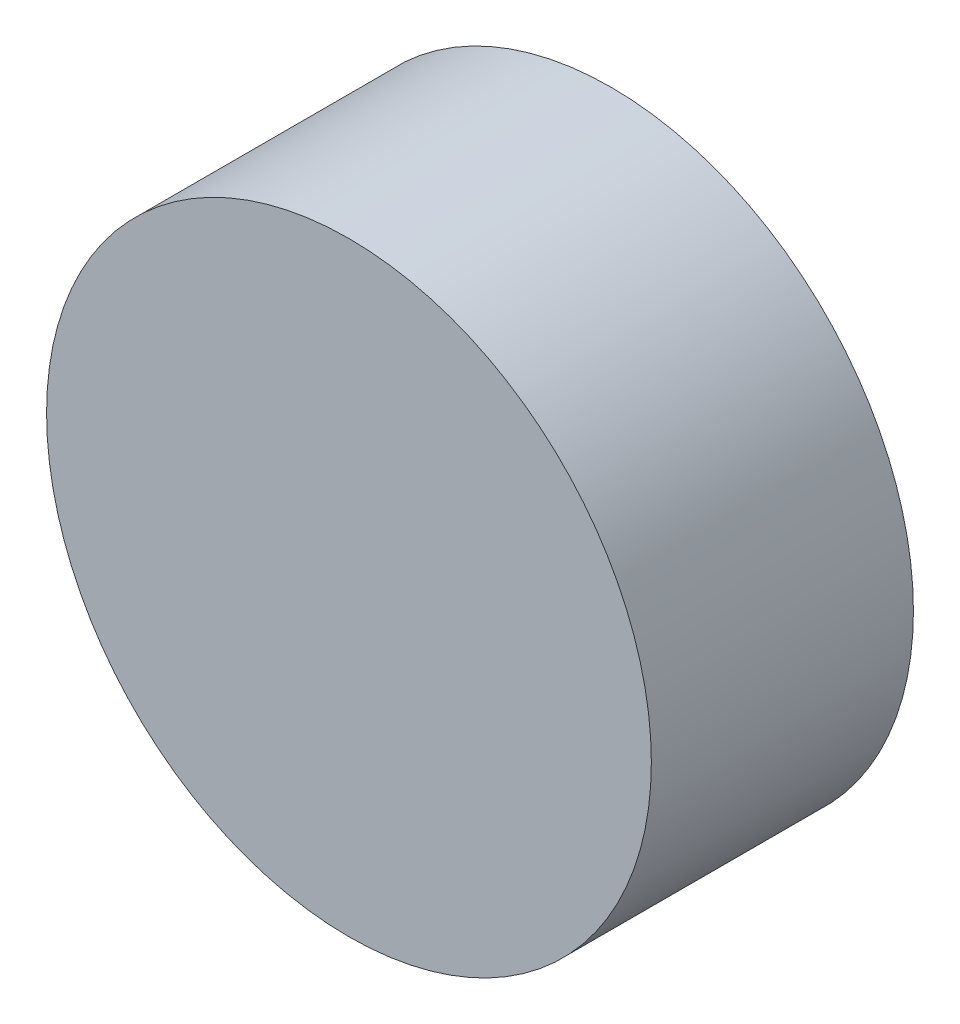
SolidWorks part; units mm, degrees
ref_plane "Front Plane" through (0, 0, 0) normal (0, 0, 1) x (1, 0, 0)
ref_plane "Top Plane" through (0, 0, 0) normal (0, 1, 0) x (1, 0, 0)
ref_plane "Right Plane" through (0, 0, 0) normal (1, 0, 0) x (0, 0, -1)
sketch "Sketch1" plane through (0, 0, 0) normal (0, 0, 1) x (1, 0, 0)
  circle A0 centre (0, 0) radius 30
  dimension "D1" = 60
extrude "Boss-Extrude1" add sketch "Sketch1" along normal blind 26
sketch "Sketch2" plane through (0, 0, 26) normal (0, 0, 1) x (1, 0, 0)
  circle A1 centre (0, 0) radius 3
  dimension "D2" = 6
extrude "Cut-Extrude1" cut sketch "Sketch2" along normal blind 10 from surface at -26 starting at face at (30, 0, 0)
